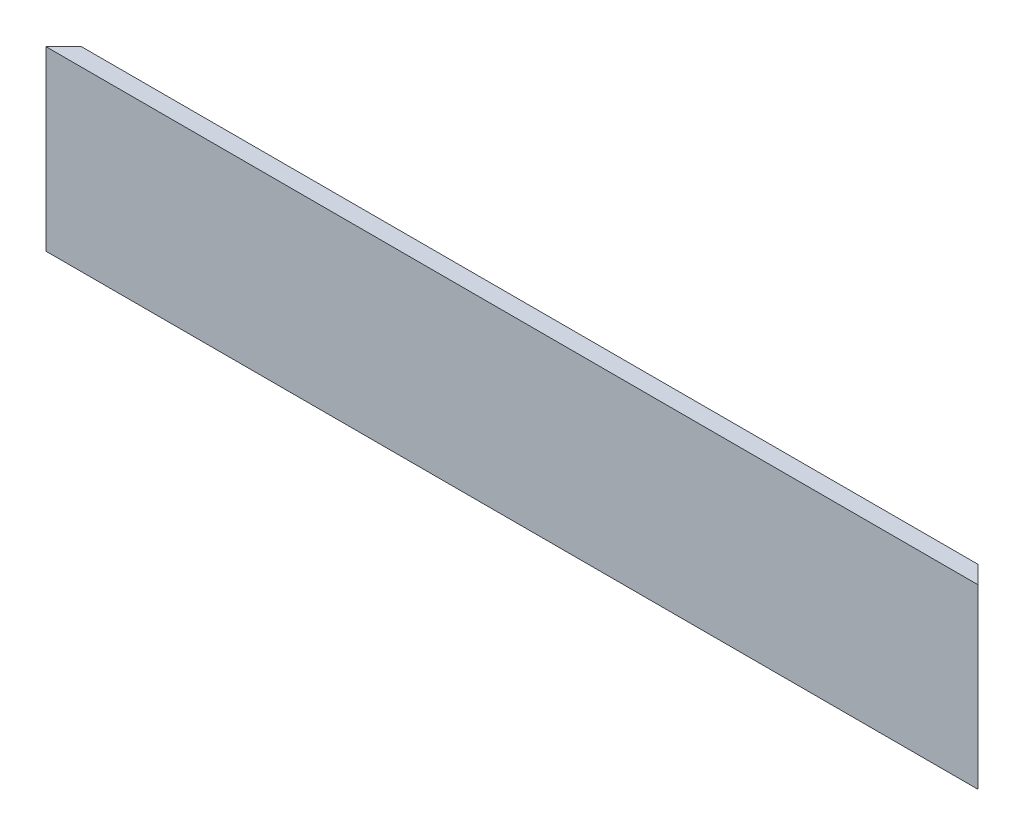
SolidWorks part; units mm, degrees
ref_plane "Alzado" through (0, 0, 0) normal (0, 0, 1) x (1, 0, 0)
ref_plane "Planta" through (0, 0, 0) normal (0, 1, 0) x (1, 0, 0)
ref_plane "Vista lateral" through (0, 0, 0) normal (1, 0, 0) x (0, 0, -1)
sketch "Croquis1" plane through (0, 0, 0) normal (0, 1, 0) x (1, 0, 0)
  line L1 (-263, 5) -> (263, 5)
  line L2 (-263, 5) -> (-263, -5)
  line L3 (-263, -5) -> (263, -5)
  line L4 (263, 5) -> (263, -5)
  line L5 (-263, 5) -> (263, -5) construction
  line L6 (-263, -5) -> (263, 5) construction
  point P0 (0, 0)
  dimension "D1" = 526
  dimension "D2" = 10
extrude "Saliente-Extruir1" add sketch "Croquis1" along normal blind 100
sketch "Croquis2" plane through (0, 100, 0) normal (0, 1, 0) x (1, 0, 0)
  line L0 (-263, -5) -> (-253, 5)
  line L1 (263, 5) -> (-263, 5) construction
  line L2 (-253, 5) -> (-263, 5)
  line L3 (-263, 5) -> (-263, -5)
  line L4 (-263, -5) -> (263, -5) construction
  line L5 (0, 5) -> (0, -5) construction
  line L6 (253, 5) -> (263, 5)
  line L7 (263, -5) -> (253, 5)
  line L8 (263, 5) -> (263, -5)
  dimension "D1" = 45
extrude "Cortar-Extruir1" cut sketch "Croquis2" against normal blind 100
sketch "Croquis3" plane through (0, 0, -5) normal (0, 0, -1) x (-1, 0, 0)
  line L0 (-263, 100) -> (-263, 0) construction
  line L1 (-263, 98.75) -> (263, 98.75)
  line L2 (-263, 98.75) -> (-263, 1.25)
  line L3 (-263, 1.25) -> (263, 1.25)
  line L4 (263, 98.75) -> (263, 1.25)
  line L5 (263, 100) -> (263, 0) construction
  line L6 (-253, 100) -> (253, 100) construction
  line L7 (-253, 0) -> (253, 0) construction
  dimension "D1" = 1.25
  dimension "D2" = 1.25
extrude "Cortar-Extruir2" cut sketch "Croquis3" against normal blind 9.25
